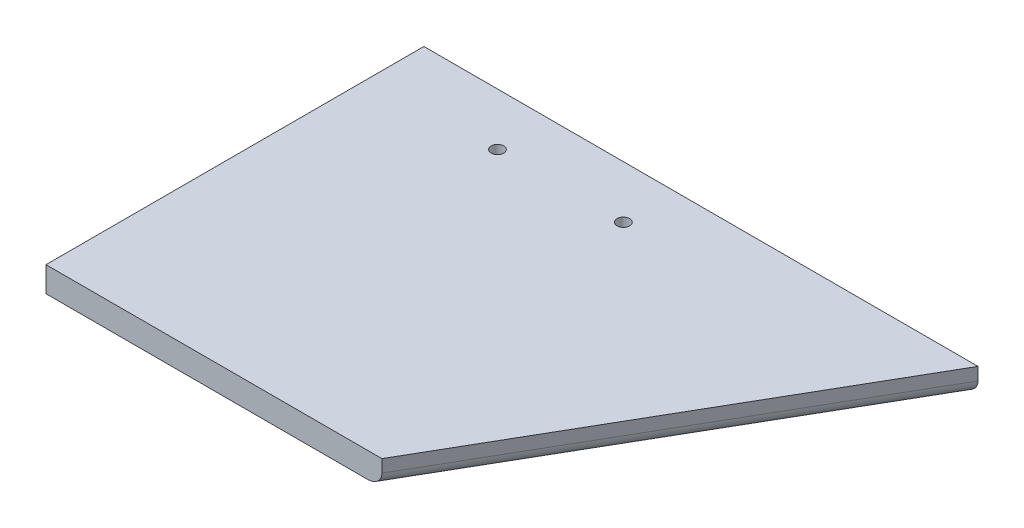
SolidWorks part; units mm, degrees
ref_plane "Front" through (0, 0, 0) normal (0, 0, 1) x (1, 0, 0)
ref_plane "Top" through (0, 0, 0) normal (0, 1, 0) x (1, 0, 0)
ref_plane "Right" through (0, 0, 0) normal (1, 0, 0) x (0, 0, -1)
sketch "Sketch1" plane through (0, 0, 0) normal (0, 1, 0) x (1, 0, 0)
  line L0 (0, 0) -> (51.9615, 90)
  line L1 (0, 0) -> (-80, 0)
  line L3 (0, 90) -> (-80, 90)
  line L4 (-80, 0) -> (-80, 90)
  line L5 (51.9615, 90) -> (0, 90)
  point P6 (0, 90)
  point P7 (0, 0)
  dimension "D1" = 80
  dimension "D2" = 90
  dimension "D3" = 120
extrude "Boss-Extrude1" add sketch "Sketch1" along normal blind 6
fillet "Fillet1" radius 3 1 edges at (25.9808, 0, -45)
sketch "Sketch2" plane through (0, 6, 0) normal (0, 1, 0) x (1, 0, 0)
  line L0 (-80, 90) -> (-80, 0) construction
  line L1 (51.9615, 90) -> (-80, 90) construction
  circle A0 centre (-50, 77.5) radius 1.5
  circle A1 centre (-20, 77.5) radius 1.5
  point P4 (0, 0)
  dimension "D1" = 3
  dimension "D2" = 30
  dimension "D3" = 30
  dimension "D4" = 12.5
extrude "Cut-Extrude1" cut sketch "Sketch2" against normal through all
